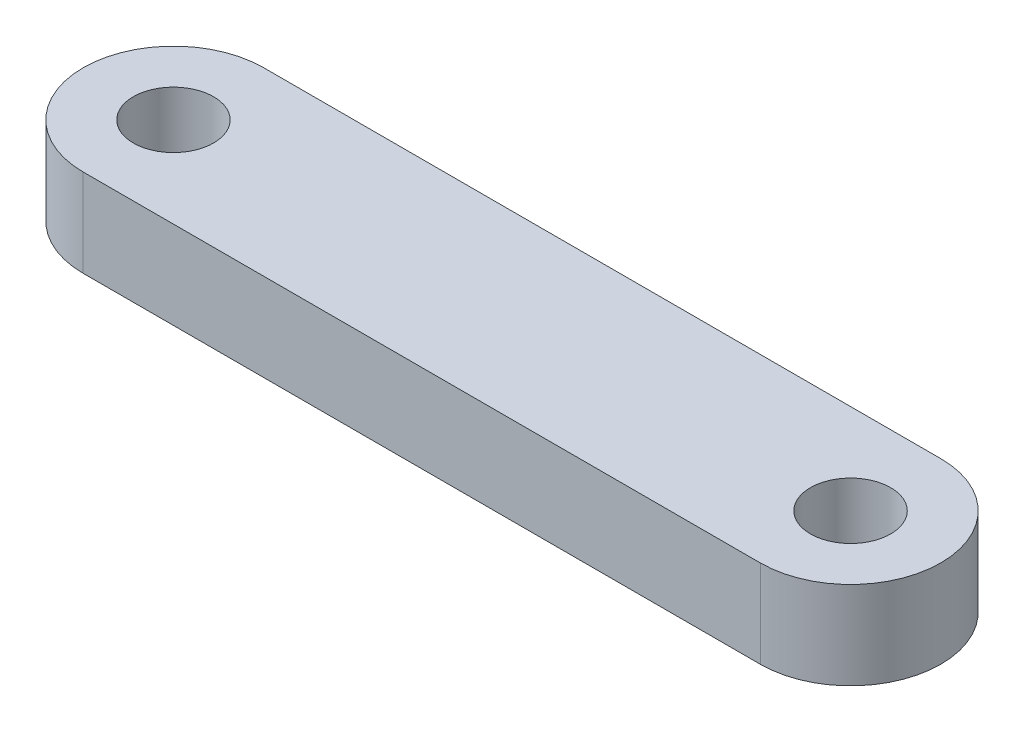
SolidWorks part; units mm, degrees
ref_plane "Front Plane" through (0, 0, 0) normal (0, 0, 1) x (1, 0, 0)
ref_plane "Top Plane" through (0, 0, 0) normal (0, 1, 0) x (1, 0, 0)
ref_plane "Right Plane" through (0, 0, 0) normal (1, 0, 0) x (0, 0, -1)
sketch "Sketch1" plane through (0, 0, 0) normal (0, 1, 0) x (1, 0, 0)
  line L0 (-27, 3.6) -> (0, 3.6)
  line L1 (0, -3.6) -> (-27, -3.6)
  circle A0 centre (0, 0) radius 1.6
  circle A1 centre (-27, 0) radius 1.6
  arc A2 (0, -3.6) -> (0, 3.6) centre (0, 0) ccw
  arc A3 (-27, 3.6) -> (-27, -3.6) centre (-27, 0) ccw
  circle A4 centre (-27, 0) radius 3.6 construction
  circle A5 centre (0, 0) radius 3.6 construction
  dimension "D2" = 3.2
  dimension "D3" = 3.2
  dimension "D1" = 27
  dimension "D4" = 2
  dimension "D5" = 2
extrude "Boss-Extrude1" add sketch "Sketch1" along normal blind 3.5 contours L1 A3 L0 A2
